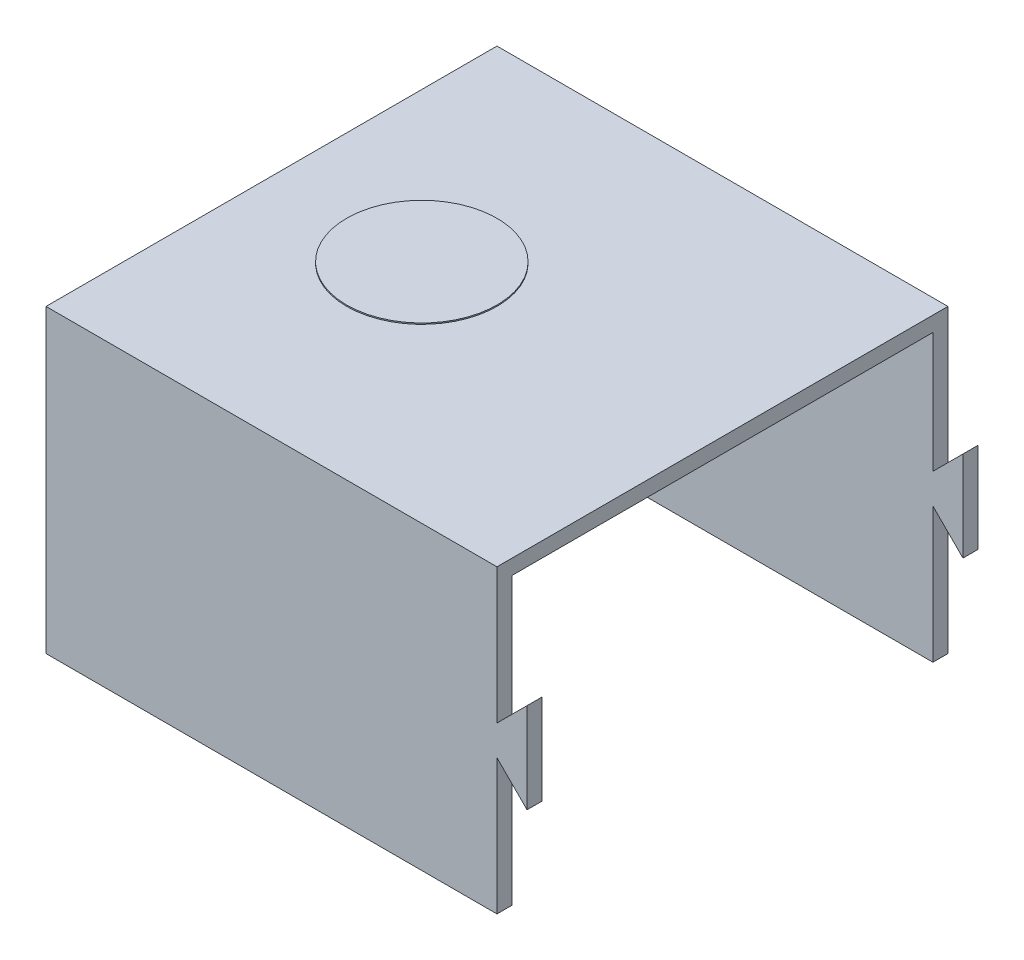
SolidWorks part; units mm, degrees
ref_plane "前视基准面" through (0, 0, 0) normal (0, 0, 1) x (1, 0, 0)
ref_plane "上视基准面" through (0, 0, 0) normal (0, 1, 0) x (1, 0, 0)
ref_plane "右视基准面" through (0, 0, 0) normal (1, 0, 0) x (0, 0, -1)
sketch "草图1" plane through (0, 0, 0) normal (0, 1, 0) x (1, 0, 0)
  line L0 (-118.1293, 58.0254) -> (31.8707, 58.0254)
  line L1 (-118.1293, 58.0254) -> (-118.1293, -91.9746)
  line L2 (31.8707, 58.0254) -> (31.8707, -91.9746)
  line L3 (-118.1293, -91.9746) -> (31.8707, -91.9746)
  dimension "D1" = 150
  dimension "D2" = 150
extrude "凸台-拉伸1" add sketch "草图1" along normal blind 100
sketch "草图4" plane through (0, 100, 0) normal (0, 1, 0) x (1, 0, 0)
  line L0 (31.8707, 58.0254) -> (-118.1293, 58.0254) construction
  line L1 (-118.1293, 58.0254) -> (-118.1293, -91.9746) construction
  circle A0 centre (-68.1293, -16.9746) radius 25
  dimension "D1" = 50
  dimension "D2" = 75
  dimension "D3" = 50
extrude "凸台-拉伸2" add sketch "草图4" along normal blind 0.4
sketch "草图5" plane through (0, 0, 0) normal (0, -1, 0) x (1, 0, 0)
  line L0 (31.8707, 86.9746) -> (-113.1293, 86.9746)
  line L1 (31.8707, 86.9746) -> (31.8707, -53.0254)
  line L2 (-113.1293, 86.9746) -> (-113.1293, -53.0254)
  line L3 (31.8707, -53.0254) -> (-113.1293, -53.0254)
  line L4 (31.8707, 91.9746) -> (31.8707, -58.0254) construction
  line L5 (-118.1293, 91.9746) -> (31.8707, 91.9746) construction
  line L6 (31.8707, -58.0254) -> (-118.1293, -58.0254) construction
  line L7 (-118.1293, -58.0254) -> (-118.1293, 91.9746) construction
  dimension "D1" = 5
  dimension "D2" = 5
  dimension "D3" = 5
extrude "切除-拉伸1" cut sketch "草图5" against normal blind 95
sketch "草图7" plane through (0, 0, 91.9746) normal (0, 0, 1) x (1, 0, 0)
  line L0 (31.8707, 55) -> (41.8707, 55)
  line L1 (31.8707, 55) -> (31.8707, 45)
  line L2 (41.8707, 55) -> (41.8707, 45)
  line L3 (31.8707, 45) -> (41.8707, 45)
  line L4 (31.8707, 100) -> (31.8707, 0) construction
  line L5 (-118.1293, 100) -> (31.8707, 100) construction
  line L6 (-118.1293, 0) -> (31.8707, 0) construction
  dimension "D1" = 10
  dimension "D2" = 45
  dimension "D3" = 45
extrude "凸台-拉伸3" add sketch "草图7" against normal blind 5
sketch "草图9" plane through (0, 0, 91.9746) normal (0, 0, 1) x (1, 0, 0)
  line L0 (31.8707, 55) -> (41.8707, 65)
  line L1 (41.8707, 65) -> (41.8707, 55)
  line L2 (41.8707, 55) -> (31.8707, 55)
  line L3 (31.8707, 45) -> (41.8707, 45)
  line L4 (41.8707, 45) -> (41.8707, 35)
  line L5 (41.8707, 35) -> (31.8707, 45)
  dimension "D1" = 45
  dimension "D2" = 45
extrude "凸台-拉伸4" add sketch "草图9" against normal blind 5
sketch "草图10" plane through (0, 0, -58.0254) normal (0, 0, -1) x (-1, 0, 0)
  line L0 (-31.8707, 55) -> (-41.8707, 55)
  line L1 (-31.8707, 55) -> (-31.8707, 45)
  line L2 (-41.8707, 55) -> (-41.8707, 45)
  line L3 (-31.8707, 45) -> (-41.8707, 45)
  line L4 (-31.8707, 100) -> (-31.8707, 0) construction
  line L5 (-31.8707, 100) -> (118.1293, 100) construction
  line L6 (-31.8707, 0) -> (118.1293, 0) construction
  point P8 (-36.8707, 55)
  dimension "D1" = 10
  dimension "D2" = 45
  dimension "D3" = 45
extrude "凸台-拉伸5" add sketch "草图10" against normal blind 5
sketch "草图11" plane through (0, 0, -58.0254) normal (0, 0, -1) x (-1, 0, 0)
  line L0 (-31.8707, 55) -> (-41.8707, 65)
  line L1 (-41.8707, 65) -> (-41.8707, 55)
  line L2 (-41.8707, 55) -> (-31.8707, 55)
  line L3 (-31.8707, 45) -> (-41.8707, 45)
  line L4 (-41.8707, 45) -> (-41.8707, 35)
  line L5 (-41.8707, 35) -> (-31.8707, 45)
  dimension "D1" = 45
  dimension "D2" = 45
extrude "凸台-拉伸6" add sketch "草图11" against normal blind 5
